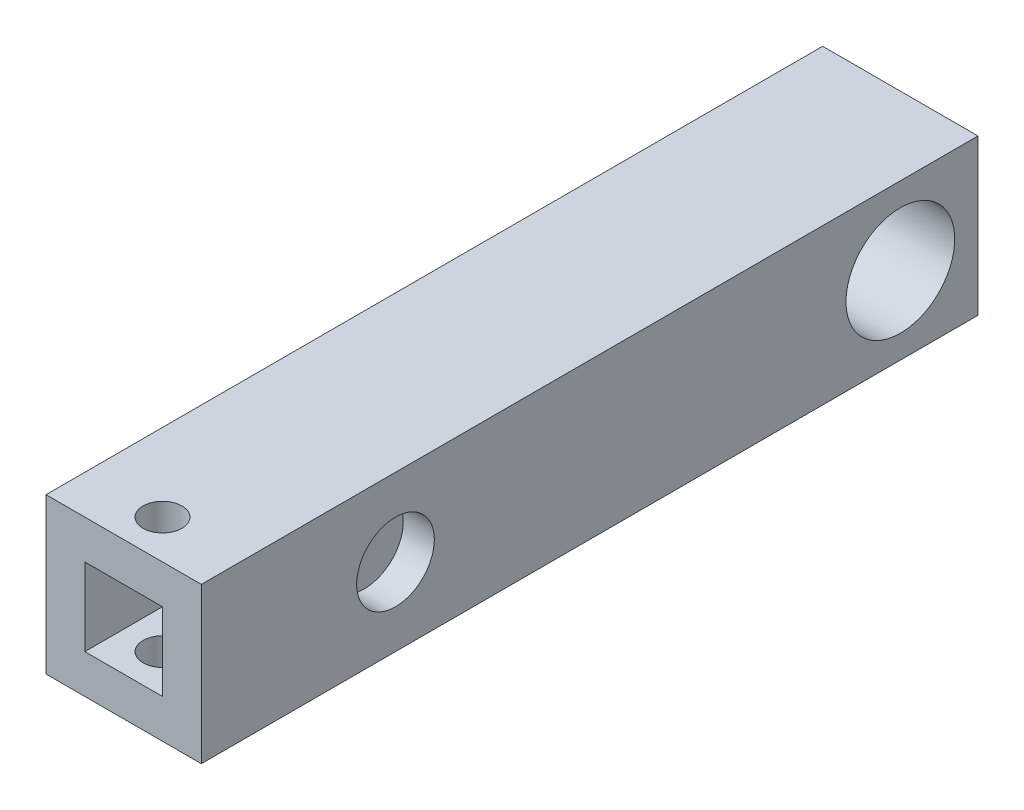
SolidWorks part; units mm, degrees
ref_plane "Front Plane" through (0, 0, 0) normal (0, 0, 1) x (1, 0, 0)
ref_plane "Top Plane" through (0, 0, 0) normal (0, 1, 0) x (1, 0, 0)
ref_plane "Right Plane" through (0, 0, 0) normal (1, 0, 0) x (0, 0, -1)
sketch "Sketch1" plane through (0, 0, 0) normal (0, 0, 1) x (1, 0, 0)
  line L1 (-100, -100) -> (100, -100)
  line L2 (-100, -100) -> (-100, 100)
  line L3 (-100, 100) -> (100, 100)
  line L4 (100, -100) -> (100, 100)
  line L5 (-100, -100) -> (100, 100) construction
  line L6 (-100, 100) -> (100, -100) construction
  point P0 (0, 0)
extrude "Boss-Extrude1" add sketch "Sketch1" along normal blind 1000
sketch "Sketch2" plane through (100, 0, 0) normal (1, 0, 0) x (0, 0, -1)
  line L0 (0, 0) -> (-100, 0) construction
  circle A0 centre (-100, 0) radius 70
extrude "Cut-Extrude1" cut sketch "Sketch2" against normal blind 300 and the other way blind 100
sketch "Sketch3" plane through (0, 0, 1000) normal (0, 0, 1) x (1, 0, 0)
  line L1 (50, 50) -> (-50, 50)
  line L2 (50, 50) -> (50, -50)
  line L3 (50, -50) -> (-50, -50)
  line L4 (-50, 50) -> (-50, -50)
  line L5 (50, 50) -> (-50, -50) construction
  line L6 (50, -50) -> (-50, 50) construction
  point P0 (0, 0)
extrude "Cut-Extrude2" cut sketch "Sketch3" against normal blind 100
sketch "Sketch4" plane through (0, -50, 0) normal (0, 1, 0) x (1, 0, 0)
  line L0 (-50, -900) -> (50, -1000) construction
  line L1 (50, -900) -> (-50, -1000) construction
  circle A0 centre (0, -950) radius 25
extrude "Cut-Extrude3" cut sketch "Sketch4" against normal blind 100 and the other way blind 183
sketch "Sketch5" plane through (100, 0, 0) normal (1, 0, 0) x (0, 0, -1)
  line L0 (-1000, 0) -> (-750, 0) construction
  line L1 (-1000, -100) -> (-1000, 100) construction
  circle A0 centre (-750, 0) radius 50
extrude "Cut-Extrude4" cut sketch "Sketch5" against normal blind 40
sketch "Sketch6" plane through (-100, 0, 0) normal (-1, 0, 0) x (0, 0, 1)
  line L0 (1000, 0) -> (750, 0) construction
  line L1 (1000, 100) -> (1000, -100) construction
  circle A0 centre (750, 0) radius 50
extrude "Cut-Extrude5" cut sketch "Sketch6" against normal blind 40
